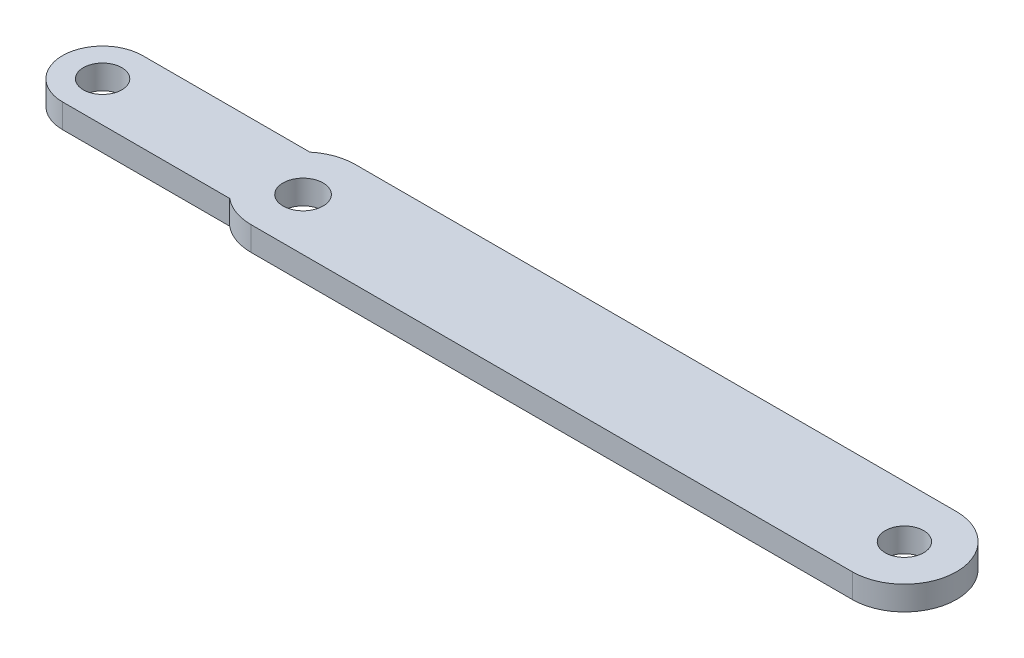
SolidWorks part; units mm, degrees
ref_plane "Front Plane" through (0, 0, 0) normal (0, 0, 1) x (1, 0, 0)
ref_plane "Top Plane" through (0, 0, 0) normal (0, 1, 0) x (1, 0, 0)
ref_plane "Right Plane" through (0, 0, 0) normal (1, 0, 0) x (0, 0, -1)
sketch "Sketch2" plane through (0, 0, 0) normal (0, 1, 0) x (1, 0, 0)
  line L1 (12.5936, 198.8185) -> (87.5936, 198.8185)
  line L3 (12.5936, 185.8185) -> (87.5936, 185.8185)
  line L4 (12.5936, 187.3185) -> (-12.4064, 187.3185)
  line L6 (12.5936, 197.3185) -> (-12.4064, 197.3185)
  arc A0 (87.5936, 198.8185) -> (87.5936, 185.8185) centre (87.5936, 192.3185) cw
  circle A1 centre (87.5936, 192.3185) radius 2.4
  arc A2 (12.5936, 198.8185) -> (12.5936, 185.8185) centre (12.5936, 192.3185) ccw
  arc A3 (-12.4064, 197.3185) -> (-12.4064, 187.3185) centre (-12.4064, 192.3185) ccw
  circle A4 centre (-12.4064, 192.3185) radius 2.4
  circle A5 centre (12.5936, 192.3185) radius 2.5
  dimension "D3" = 4.8
  dimension "D7" = 4.8
  dimension "D8" = 5
  dimension "D1" = 75
  dimension "D2" = 13
  dimension "D4" = 1.5
  dimension "D5" = 1.5
  dimension "D6" = 25
extrude "Boss-Extrude1" add sketch "Sketch2" along normal blind 3
